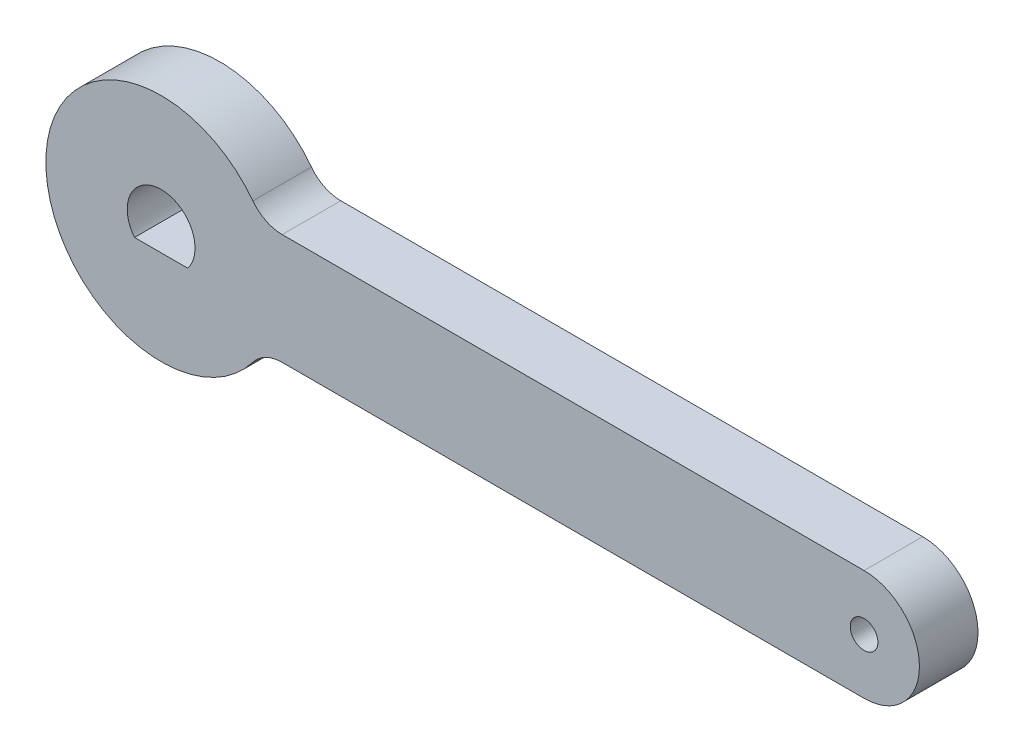
SolidWorks part; units mm, degrees
ref_plane "Plan de face" through (0, 0, 0) normal (0, 0, 1) x (1, 0, 0)
ref_plane "Plan de dessus" through (0, 0, 0) normal (0, 1, 0) x (1, 0, 0)
ref_plane "Plan de droite" through (0, 0, 0) normal (1, 0, 0) x (0, 0, -1)
sketch "Esquisse1" plane through (0, 0, 0) normal (0, 0, 1) x (1, 0, 0)
  line L0 (0, 0) -> (76.2, 0) construction
  line L1 (0, 6) -> (76.2, 6)
  line L2 (0, -6) -> (76.2, -6)
  arc A0 (0, 6) -> (0, -6) centre (0, 0) ccw
  arc A1 (76.2, -6) -> (76.2, 6) centre (76.2, 0) ccw
  point P3 (38.1, 0)
  dimension "D2" = 6
  dimension "D1" = 76.2
extrude "Boss.-Extru.1" add sketch "Esquisse1" along normal blind 6.35
sketch "Esquisse4" plane through (0, 0, 6.35) normal (0, 0, 1) x (1, 0, 0)
  circle A0 centre (0, 0) radius 12.5
  dimension "D1" = 25
extrude "Boss.-Extru.2" add sketch "Esquisse4" against normal blind 6.35
sketch "Esquisse2" plane through (0, 0, 6.35) normal (0, 0, 1) x (1, 0, 0)
  line L0 (-2.8862, -2.275) -> (2.8862, -2.275)
  arc A0 (2.8862, -2.275) -> (-2.8862, -2.275) centre (0, 0) ccw
  dimension "D1" = 7.35
  dimension "D2" = 2.275
extrude "Enlèv. mat.-Extru.1" cut sketch "Esquisse2" against normal up to next
sketch "Esquisse3" plane through (0, 0, 6.35) normal (0, 0, 1) x (1, 0, 0)
  circle A0 centre (76.2, 0) radius 1.5
  dimension "D1" = 3
extrude "Enlèv. mat.-Extru.2" cut sketch "Esquisse3" against normal blind 6.35
fillet "Congé1" radius 4 2 edges at (10.9659, -6, 3.175) (10.9659, 6, 3.175)
